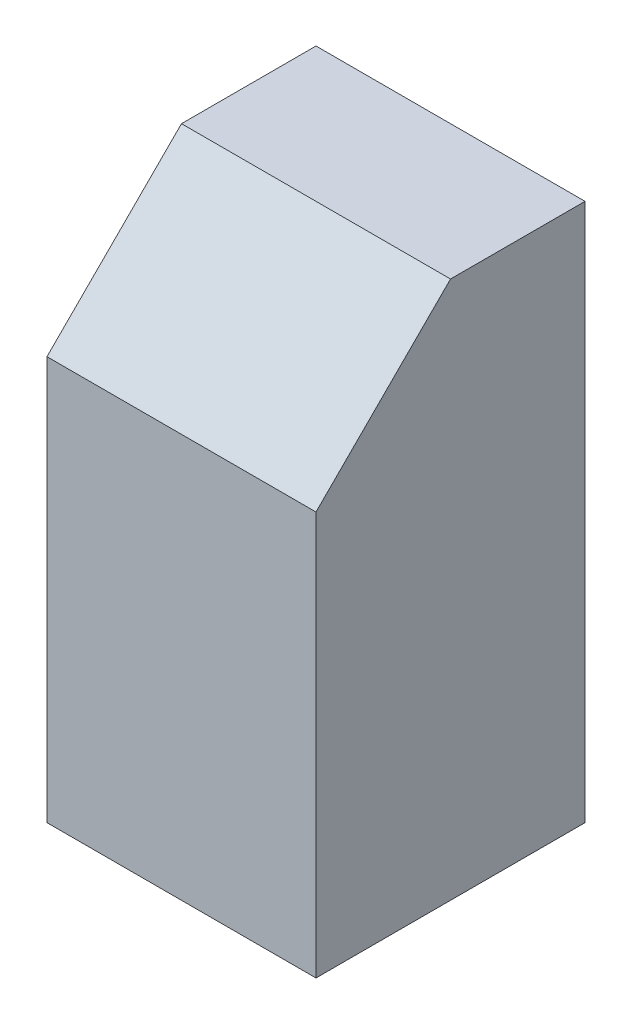
SolidWorks part; units mm, degrees
ref_plane "Front Plane" through (0, 0, 0) normal (0, 0, 1) x (1, 0, 0)
ref_plane "Top Plane" through (0, 0, 0) normal (0, 1, 0) x (1, 0, 0)
ref_plane "Right Plane" through (0, 0, 0) normal (1, 0, 0) x (0, 0, -1)
sketch "Sketch1" plane through (0, 0, 0) normal (0, 1, 0) x (1, 0, 0)
  line L1 (-250, -250) -> (250, -250)
  line L2 (-250, -250) -> (-250, 250)
  line L3 (-250, 250) -> (250, 250)
  line L4 (250, -250) -> (250, 250)
  line L5 (-250, -250) -> (250, 250) construction
  line L6 (-250, 250) -> (250, -250) construction
  point P0 (0, 0)
  dimension "D1" = 500
  dimension "D2" = 500
extrude "Boss-Extrude1" add sketch "Sketch1" along normal blind 1000
sketch "Sketch3" plane through (250, 0, 0) normal (1, 0, 0) x (0, 0, -1)
  line L0 (0, 1000) -> (-250, 750)
  line L4 (-250, 0) -> (250, 0)
  line L5 (250, 0) -> (250, 1000)
  line L6 (250, 1000) -> (-250, 1000)
  line L7 (-250, 1000) -> (-250, 0)
  line L8 (-250, 0) -> (250, 0)
  line L9 (250, 0) -> (250, 1000)
  line L10 (250, 1000) -> (-250, 1000)
  line L11 (-250, 1000) -> (-250, 0)
  line M8 (250, 1000) -> (-250, 1000)
  line M9 (-250, 1000) -> (-250, 0)
  dimension "D2" = 45
  dimension "D1" = 0
extrude "Cut-Extrude1" cut sketch "Sketch3" against normal up to next contours L0 M8 M9
